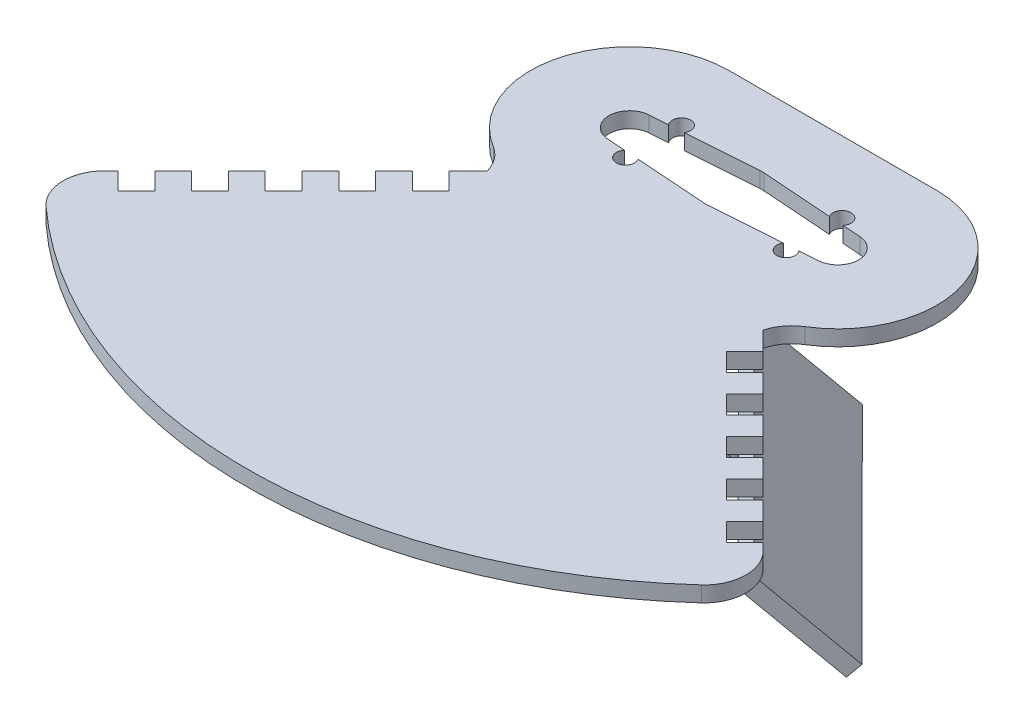
SolidWorks part; units mm, degrees
ref_plane "前视基准面" through (0, 0, 0) normal (0, 0, 1) x (1, 0, 0)
ref_plane "上视基准面" through (0, 0, 0) normal (0, 1, 0) x (1, 0, 0)
ref_plane "右视基准面" through (0, 0, 0) normal (1, 0, 0) x (0, 0, -1)
sketch "草图1" plane through (0, 0, 0) normal (0, 1, 0) x (1, 0, 0)
  line L1 (-90, 61.7378) -> (90, 61.7378)
  line L2 (-90, 61.7378) -> (-90, -61.7378)
  line L3 (-90, -61.7378) -> (90, -61.7378)
  line L4 (90, 61.7378) -> (90, -61.7378)
  line L5 (-90, 61.7378) -> (90, -61.7378) construction
  line L6 (-90, -61.7378) -> (90, 61.7378) construction
  point P0 (0, 0)
  dimension "D1" = 180
extrude "凸台-拉伸1" add sketch "草图1" along normal blind 3
sketch "草图2" plane through (0, 3, 0) normal (0, 1, 0) x (1, 0, 0)
  line L4 (63.3932, -4.572) -> (17.6608, 41.1604)
  line L5 (-17.3899, 41.1604) -> (-63.1223, -4.572)
  arc A12 (17.6608, 41.1604) -> (8.5192, 41.8167) centre (12.711, 36.2107) ccw
  arc A13 (-8.2483, 41.8167) -> (8.5192, 41.8167) centre (0.1354, 53.0289) ccw
  arc A14 (-8.2483, 41.8167) -> (-17.3899, 41.1604) centre (-12.4402, 36.2107) ccw
  arc A15 (-63.1223, -4.572) -> (-62.8516, -16.144) centre (-57.4654, -10.2288) ccw
  arc A16 (-62.8516, -16.144) -> (63.1225, -16.144) centre (0.1354, 53.0289) ccw
  arc A17 (63.1225, -16.144) -> (63.3932, -4.572) centre (57.7363, -10.2288) ccw
extrude "切除-拉伸1" cut sketch "草图2" against normal blind 10 flip side to cut
ref_plane "基准面1" through (22.3395, 0, -22.3395) normal (0.7071, 0, -0.7071) x (-0.7071, 0, -0.7071)
ref_plane "基准面2" through (11.1698, 15.7964, -11.1698) normal (-0.5, -0.7071, 0.5) x (-0.866, 0.4082, -0.2887)
sketch "草图4" plane through (11.1698, 15.7964, -11.1698) normal (-0.5, -0.7071, 0.5) x (-0.866, 0.4082, -0.2887)
  line L0 (-42.8876, 35.135) -> (-23.8864, 8.3576)
  line L1 (-42.8876, 35.135) -> (-44.5889, 33.9277)
  line L2 (-23.8864, 8.3576) -> (-25.5877, 7.1504)
  line L3 (-44.5889, 33.9277) -> (-25.5877, 7.1504)
  line L4 (-42.8876, 35.135) -> (-25.5877, 7.1504) construction
  line L5 (-23.8864, 8.3576) -> (-44.5889, 33.9277) construction
  point P1 (-34.2376, 21.1427)
extrude "凸台-拉伸3" add sketch "草图4" along normal mid plane 3
sketch "草图5" plane through (11.9198, 16.8571, -11.9198) normal (0.5, 0.7071, -0.5) x (0.866, -0.4082, 0.2887)
  line L0 (5.3055, 33.2627) -> (23.4408, 58.8557)
  line L2 (23.4408, 58.8557) -> (73.424, 23.4375)
  line L3 (55.2887, -2.1556) -> (73.424, 23.4375)
  line L4 (30.2971, 15.5535) -> (73.424, 23.4375) construction
  line L5 (23.4408, 58.8557) -> (30.2971, 15.5535) construction
  line L6 (55.2887, -2.1556) -> (5.3055, 33.2627)
  point P1 (30.2971, 15.5535)
extrude "凸台-拉伸4" add sketch "草图5" along normal blind 3
sketch "草图6" plane through (13.4198, 18.9784, -13.4198) normal (0.5, 0.7071, -0.5) x (0.866, -0.4082, 0.2887)
  line L0 (17.3329, 50.236) -> (67.3161, 14.8178)
  line L4 (5.3055, 33.2627) -> (55.2887, -2.1556)
  line L5 (55.2887, -2.1556) -> (73.424, 23.4375)
  line L6 (73.424, 23.4375) -> (23.4408, 58.8557)
  line L7 (23.4408, 58.8557) -> (5.3055, 33.2627)
  line L9 (67.3161, 14.8178) -> (73.424, 23.4375)
  line L10 (73.424, 23.4375) -> (23.4408, 58.8557)
  line L11 (23.4408, 58.8557) -> (17.3329, 50.236)
  dimension "D1" = 0
extrude "切除-拉伸2" cut sketch "草图6" against normal blind 13
mirror "镜向2" about plane through (0, 0, 0) normal (1, 0, 0) of "切除-拉伸2", "凸台-拉伸4", "凸台-拉伸3"
sketch "草图7" plane through (0, 3, 0) normal (0, 1, 0) x (1, 0, 0)
  line L4 (-19.8646, 53.0289) -> (20.1354, 53.0289) construction
  line L5 (-19.8646, 72.0893) -> (20.1354, 72.0893)
  line L7 (28.6492, 24.5152) -> (-28.3783, 24.5152)
  line L8 (20.4154, 57.0191) -> (16.8753, 57.2675)
  line L9 (-0.2426, 58.4157) -> (-13.8157, 57.4632)
  line L10 (-20.1446, 49.0387) -> (-16.6045, 48.7903)
  line L11 (0.5134, 47.6422) -> (14.0865, 48.5946)
  line L12 (0.1354, 60.5534) -> (0.1354, 53.7988) construction
  line L13 (0.1354, 53.0289) -> (-6.309, 53.0289) construction
  line L14 (-16.6045, 57.2675) -> (-20.1446, 57.0191)
  line L15 (-13.8157, 48.5946) -> (-0.2426, 47.6422)
  line L16 (60.5647, -7.4004) -> (14.8324, 38.332) construction
  line L17 (16.8753, 48.7903) -> (20.4154, 49.0387)
  line L19 (14.0865, 57.4632) -> (0.5134, 58.4157)
  arc A1 (-13.8157, 57.4632) -> (-16.6045, 57.2675) centre (-15.2838, 58.4157) ccw
  arc A2 (14.0865, 57.4632) -> (16.8753, 57.2675) centre (15.5546, 58.4157) cw
  arc A3 (14.0865, 48.5946) -> (16.8753, 48.7903) centre (15.5546, 47.6422) ccw
  arc A4 (-13.8157, 48.5946) -> (-16.6045, 48.7903) centre (-15.2838, 47.6422) cw
  arc A5 (-19.8646, 72.0893) -> (-29.8282, 36.7801) centre (-19.8646, 53.0289) ccw
  arc A6 (30.099, 36.7801) -> (20.1354, 72.0893) centre (20.1354, 53.0289) ccw
  arc A7 (-28.3783, 24.5152) -> (-29.8282, 36.7801) centre (-33.9391, 30.076) ccw
  arc A8 (0.5134, 58.4157) -> (-0.2426, 58.4157) centre (0.1354, 53.0289) ccw
  arc A9 (-20.1446, 57.0191) -> (-20.1446, 49.0387) centre (-19.8646, 53.0289) ccw
  arc A10 (-0.2426, 47.6422) -> (0.5134, 47.6422) centre (0.1354, 53.0289) ccw
  arc A11 (20.4154, 49.0387) -> (20.4154, 57.0191) centre (20.1354, 53.0289) ccw
  arc A16 (28.6492, 24.5152) -> (30.099, 36.7801) centre (34.21, 30.076) cw
  point P6 (0.1354, 53.0289)
  dimension "D1" = 3.5
extrude "凸台-拉伸5" add sketch "草图7" against normal up to surface (3 mm away) up to face at (-33.4579, 0, -11.2211)
sketch "草图8" plane through (0, 3, 0) normal (0, 1, 0) x (1, 0, 0)
  line L0 (54.9187, -3.1685) -> (58.4542, -6.7041)
  line L1 (58.4542, -6.7041) -> (61.9897, -3.1685)
  line L2 (63.3932, -4.572) -> (26.6344, 32.1868) construction
  line L3 (0, 30.9737) -> (0, -30.2452) construction
  line L4 (61.9897, -3.1685) -> (58.4542, 0.367)
  line L5 (58.4542, 0.367) -> (54.9187, -3.1685)
  line L6 (51.3831, 7.4381) -> (47.8476, 3.9025)
  line L7 (47.8476, 3.9025) -> (51.3831, 0.367)
  line L8 (51.3831, 0.367) -> (54.9187, 3.9025)
  line L9 (54.9187, 3.9025) -> (51.3831, 7.4381)
  line L10 (44.312, 14.5091) -> (40.7765, 10.9736)
  line L11 (40.7765, 10.9736) -> (44.312, 7.4381)
  line L12 (44.312, 7.4381) -> (47.8476, 10.9736)
  line L13 (47.8476, 10.9736) -> (44.312, 14.5091)
  line L14 (37.241, 21.5802) -> (33.7054, 18.0447)
  line L15 (33.7054, 18.0447) -> (37.241, 14.5091)
  line L16 (37.241, 14.5091) -> (40.7765, 18.0447)
  line L17 (40.7765, 18.0447) -> (37.241, 21.5802)
  line L18 (30.1699, 28.6513) -> (26.6344, 25.1157)
  line L19 (26.6344, 25.1157) -> (30.1699, 21.5802)
  line L20 (30.1699, 21.5802) -> (33.7054, 25.1157)
  line L21 (33.7054, 25.1157) -> (30.1699, 28.6513)
  line L22 (58.4542, 0.367) -> (51.3831, 7.4381) construction
  line L23 (-58.4542, 0.367) -> (-51.3831, 7.4381) construction
  line L24 (-33.7054, 25.1157) -> (-30.1699, 28.6513)
  line L25 (-30.1699, 21.5802) -> (-33.7054, 25.1157)
  line L26 (-26.6344, 25.1157) -> (-30.1699, 21.5802)
  line L27 (-30.1699, 28.6513) -> (-26.6344, 25.1157)
  line L28 (-40.7765, 18.0447) -> (-37.241, 21.5802)
  line L29 (-37.241, 14.5091) -> (-40.7765, 18.0447)
  line L30 (-33.7054, 18.0447) -> (-37.241, 14.5091)
  line L31 (-37.241, 21.5802) -> (-33.7054, 18.0447)
  line L32 (-47.8476, 10.9736) -> (-44.312, 14.5091)
  line L33 (-44.312, 7.4381) -> (-47.8476, 10.9736)
  line L34 (-40.7765, 10.9736) -> (-44.312, 7.4381)
  line L35 (-44.312, 14.5091) -> (-40.7765, 10.9736)
  line L36 (-54.9187, 3.9025) -> (-51.3831, 7.4381)
  line L37 (-51.3831, 0.367) -> (-54.9187, 3.9025)
  line L38 (-47.8476, 3.9025) -> (-51.3831, 0.367)
  line L39 (-51.3831, 7.4381) -> (-47.8476, 3.9025)
  line L40 (-58.4542, 0.367) -> (-54.9187, -3.1685)
  line L41 (-61.9897, -3.1685) -> (-58.4542, 0.367)
  line L42 (-58.4542, -6.7041) -> (-61.9897, -3.1685)
  line L43 (-54.9187, -3.1685) -> (-58.4542, -6.7041)
  dimension "D3" = 5
  dimension "D5" = 10
  dimension "D4" = 5
extrude "切除-拉伸4" cut sketch "草图8" against normal blind 5
